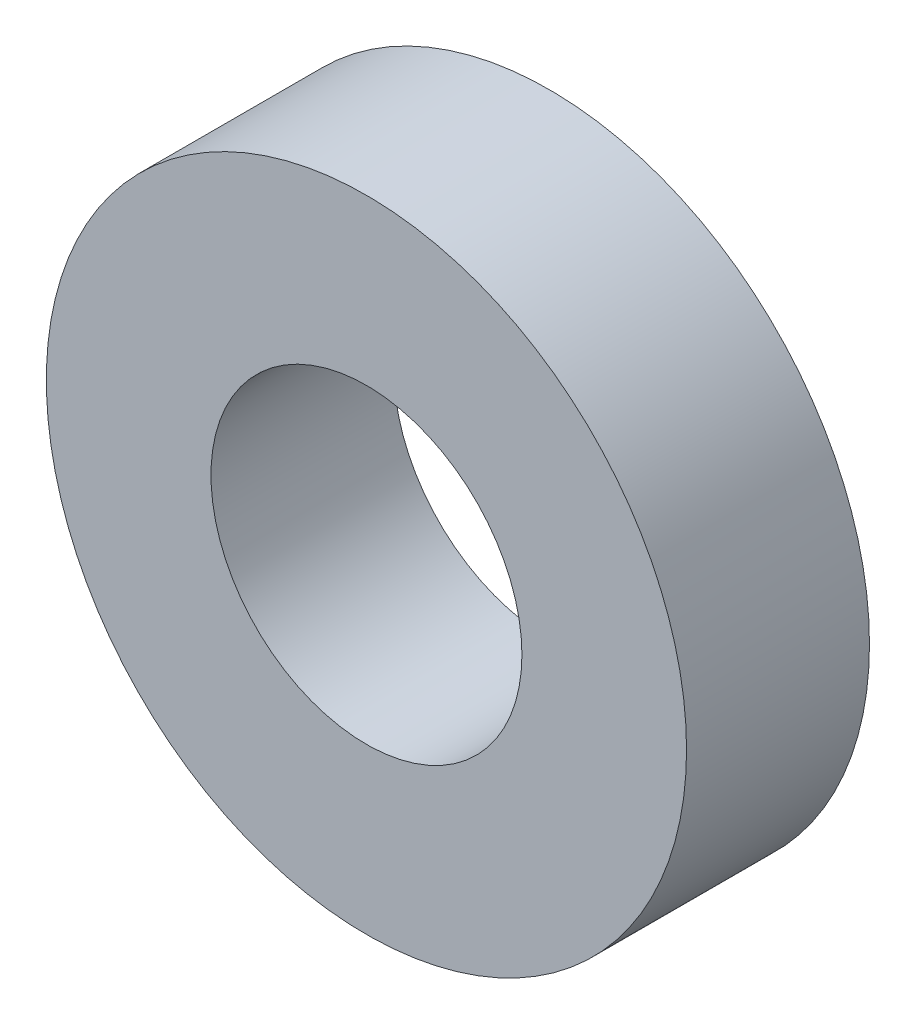
SolidWorks part; units mm, degrees
ref_plane "Спереди" through (0, 0, 0) normal (0, 0, 1) x (1, 0, 0)
ref_plane "Сверху" through (0, 0, 0) normal (0, 1, 0) x (1, 0, 0)
ref_plane "Справа" through (0, 0, 0) normal (1, 0, 0) x (0, 0, -1)
sketch "Эскиз1" plane through (0, 0, 0) normal (0, 0, 1) x (1, 0, 0)
  circle A0 centre (0, 0) radius 17.5
  circle A1 centre (0, 0) radius 8.5
extrude "Rear_bearing" add sketch "Эскиз1" along normal blind 10 from offset 47
